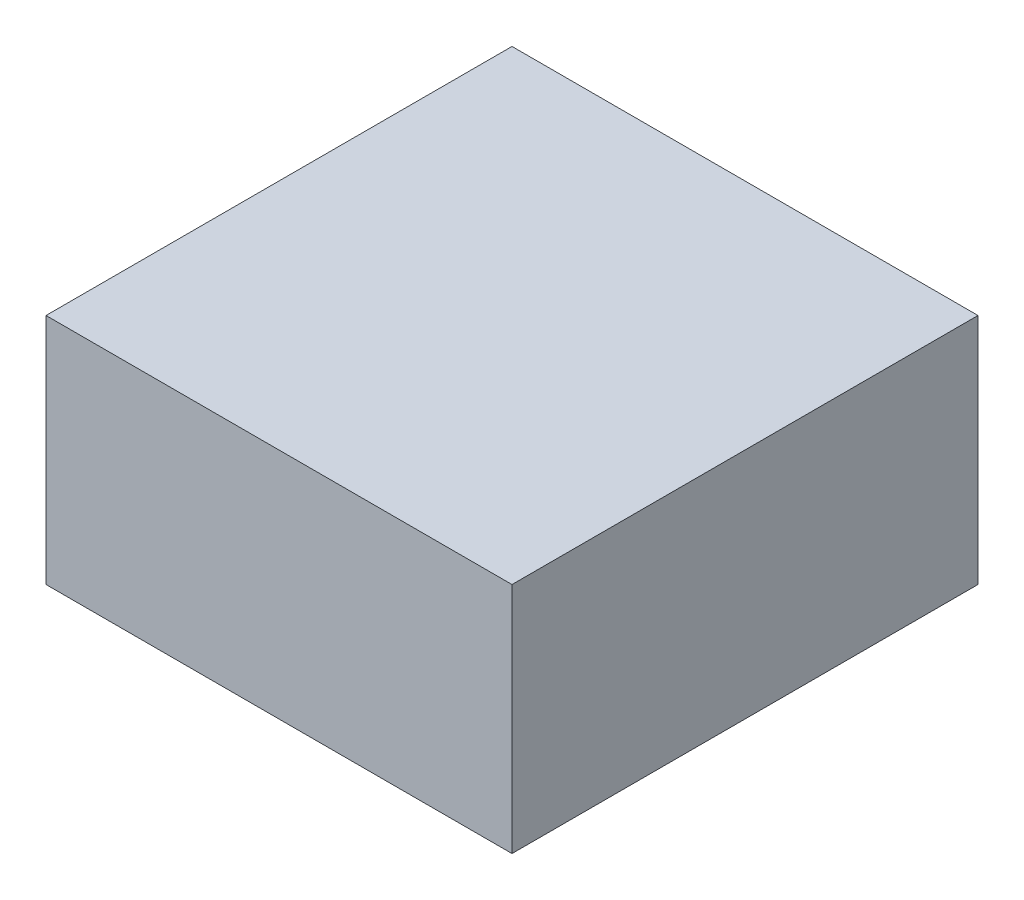
SolidWorks part; units mm, degrees
ref_plane "前视基准面" through (0, 0, 0) normal (0, 0, 1) x (1, 0, 0)
ref_plane "上视基准面" through (0, 0, 0) normal (0, 1, 0) x (1, 0, 0)
ref_plane "右视基准面" through (0, 0, 0) normal (1, 0, 0) x (0, 0, -1)
other "Configuration Table"
sketch "草图1" plane through (0, 0, 0) normal (0, 1, 0) x (1, 0, 0)
  line L1 (-20, 20) -> (20, 20)
  line L2 (-20, 20) -> (-20, -20)
  line L3 (-20, -20) -> (20, -20)
  line L4 (20, 20) -> (20, -20)
  line L5 (-20, 20) -> (20, -20) construction
  line L6 (-20, -20) -> (20, 20) construction
  point P0 (0, 0)
  dimension "D1" = 40
  dimension "D2" = 40
extrude "凸台-拉伸1" add sketch "草图1" along normal blind 20
sketch "草图2" plane through (0, 0, 0) normal (0, -1, 0) x (1, 0, 0)
  text T0 "摄像头" font "宋体" height 3.5
